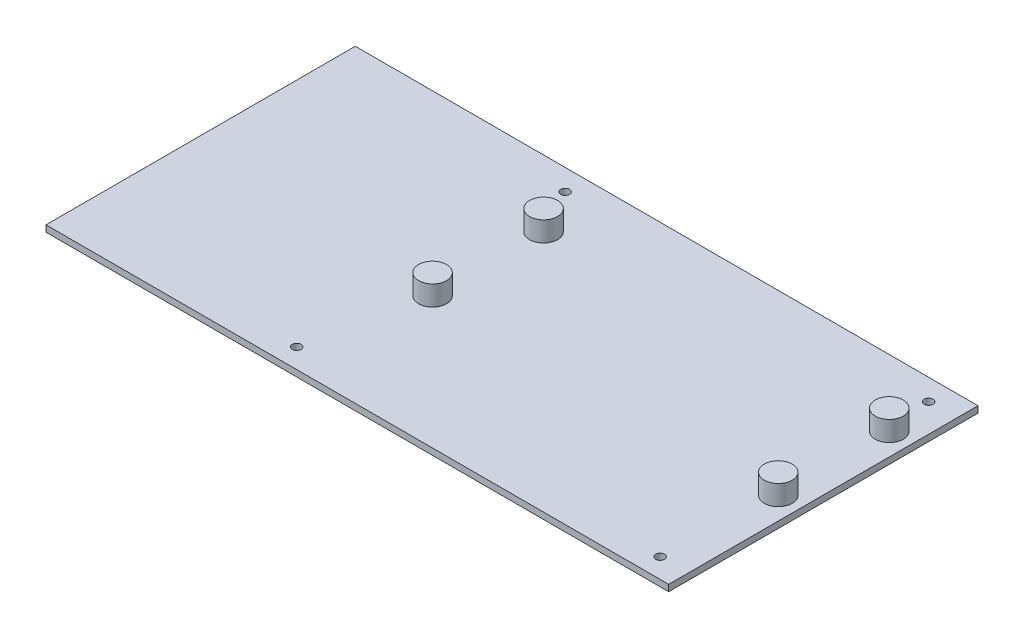
SolidWorks part; units mm, degrees
ref_plane "Front Plane" through (0, 0, 0) normal (0, 0, 1) x (1, 0, 0)
ref_plane "Top Plane" through (0, 0, 0) normal (0, 1, 0) x (1, 0, 0)
ref_plane "Right Plane" through (0, 0, 0) normal (1, 0, 0) x (0, 0, -1)
sketch "Sketch1" plane through (0, 0, 0) normal (0, 1, 0) x (1, 0, 0)
  line L1 (0, 0) -> (155, 0)
  line L2 (0, 0) -> (0, -77)
  line L3 (0, -77) -> (155, -77)
  line L4 (155, 0) -> (155, -77)
  dimension "D1" = 77
  dimension "D2" = 155
extrude "Boss-Extrude1" add sketch "Sketch1" along normal blind 1.6
sketch "Sketch2" plane through (0, 1.6, 0) normal (0, 1, 0) x (1, 0, 0)
  line L0 (155, -77) -> (155, 0) construction
  line L1 (155, -48.7936) -> (57.8486, -48.7936)
  line L2 (155, -48.7936) -> (155, -11.9128)
  line L3 (155, -11.9128) -> (57.8486, -11.9128)
  line L4 (57.8486, -48.7936) -> (57.8486, -11.9128)
  line L6 (155, 0) -> (0, 0) construction
  line L7 (106.4243, -48.7936) -> (106.4243, -11.9128) construction
  line L8 (57.8486, -30.3532) -> (155, -30.3532) construction
  line L9 (155, -30.3532) -> (155.279, -29.6325) construction
  circle A0 centre (63.3989, -16.5383) radius 3.4758
  circle A1 centre (149.4497, -16.5383) radius 3.4758
  circle A2 centre (149.4497, -44.1681) radius 3.4758
  circle A3 centre (63.3989, -44.1681) radius 3.4758
  dimension "D4" = 6.9516
  dimension "D1" = 97.1514
  dimension "D2" = 36.8808
  dimension "D3" = 11.9128
  dimension "D8" = 4.6255
  dimension "D9" = 5.5503
extrude "Boss-Extrude3" add sketch "Sketch2" along normal blind 5 contours A0 | A3 | A1 | A2
hole_wizard "M2 Clearance Hole1" positions "Sketch4" profile "Sketch5" hole size "M2" standard "ISO" end condition through all
sketch "Sketch4" plane through (0, 1.6, 0) normal (0, 1, 0) x (1, 0, 0)
  point P0 (147.9946, -5.2817)
  point P2 (147.9946, -72.1143)
  point P4 (57.4976, -72.1143)
  point P6 (57.4976, -5.2817)
sketch "Sketch5" plane through (147.9946, 1.6, 5.2817) normal (1, 0, 0) x (0, 0, 1)
  line L0 (0, 0) -> (0, 1.6)
  line L1 (0, 1.6) -> (1.1, 1.6)
  line L2 (1.1, 1.6) -> (1.1, 0)
  line L5 (1.1, 0) -> (0, 0)
  line L11 (0, -6.35) -> (0, 107.95) construction
  dimension "Thru Hole Dia." = 2.2
  dimension "Thru Hole Depth" = 1.6
